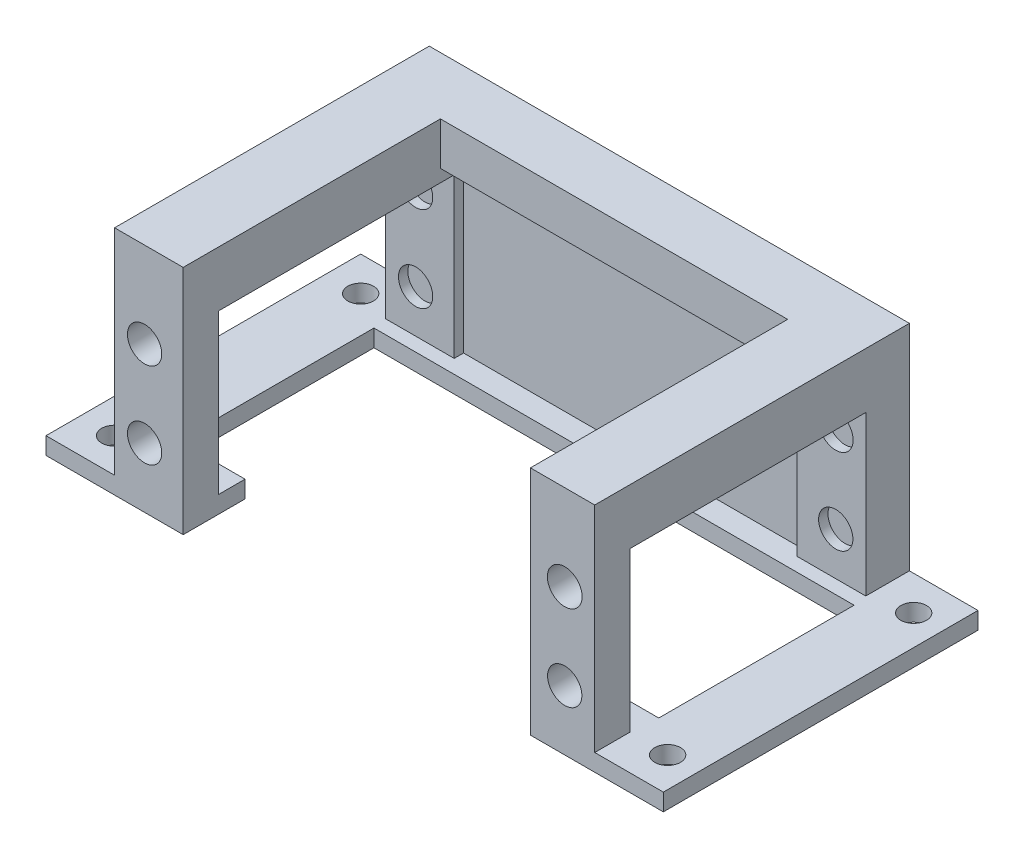
SolidWorks part; units mm, degrees
ref_plane "前视基准面" through (0, 0, 0) normal (0, 0, 1) x (1, 0, 0)
ref_plane "上视基准面" through (0, 0, 0) normal (0, 1, 0) x (1, 0, 0)
ref_plane "右视基准面" through (0, 0, 0) normal (1, 0, 0) x (0, 0, -1)
other "Configuration Table"
sketch "草图1" plane through (0, 0, 0) normal (0, 1, 0) x (1, 0, 0)
  line L1 (0, 0) -> (40, 0)
  line L2 (0, 0) -> (0, 40)
  line L3 (0, 40) -> (40, 40)
  line L4 (40, 0) -> (40, 40)
  dimension "D1" = 40
  dimension "D2" = 40
extrude "凸台-拉伸1" add sketch "草图1" along normal blind 20
sketch "草图2" plane through (0, 0, 0) normal (0, 0, 1) x (1, 0, 0)
  line L0 (0, 10) -> (10, 10)
  line L1 (0, 20) -> (0, 0) construction
  circle A0 centre (10, 10) radius 3
  dimension "D2" = 6
  dimension "D1" = 10
extrude "凸台-拉伸2" add sketch "草图2" along normal blind 4.5
ref_plane "基准面1" through (0, 0, -12.3) normal (0, 0, -1) x (-1, 0, 0)
sketch "草图4" plane through (0, 0, -12.3) normal (0, 0, -1) x (-1, 0, 0)
  line L0 (-1040, 10) -> (48960, 10) construction
  line L1 (-40, 20) -> (-48, 20)
  line L2 (-40, 20) -> (-40, 0)
  line L3 (-40, 0) -> (-48, 0)
  line L4 (-48, 20) -> (-48, 0)
  line L5 (-40, 20) -> (-44.5, 20)
  line L6 (-40, 20) -> (-40, 15)
  line L7 (-40, 15) -> (-44.5, 15)
  line L8 (-44.5, 20) -> (-44.5, 15)
  line L9 (-20, -980) -> (-20, 49020) construction
  line L10 (-40, 20) -> (0, 20) construction
  line L11 (0, 20) -> (0, 0)
  line L12 (0, 0) -> (8, 0)
  line L13 (8, 20) -> (8, 0)
  line L14 (0, 20) -> (8, 20)
  circle A0 centre (-44.5, 15) radius 2
  circle A1 centre (-44.5, 5) radius 2
  circle A2 centre (4.5, 5) radius 2
  circle A3 centre (4.5, 15) radius 2
  point P11 (-40, 10)
  point P19 (-20, 20)
  dimension "D5" = 4
  dimension "D1" = 20
  dimension "D2" = 8
  dimension "D3" = 4.5
  dimension "D4" = 5
extrude "凸台-拉伸4" add sketch "草图4" against normal blind 2.7 contours A0 L8 L1 L4 L3 L2 L7 A1 | A0 L7 L2 L1 L8 | L14 L11 L12 L13 A2 A3
sketch "草图5" plane through (0, 0, 0) normal (-1, 0, 0) x (0, 0, 1)
  line L0 (-40, 10) -> (-35, 10)
  line L1 (-40, 20) -> (-40, 0) construction
  line L3 (-37, 6.5) -> (-33, 6.5)
  line L4 (-37, 6.5) -> (-37, 13.5)
  line L5 (-37, 13.5) -> (-33, 13.5)
  line L6 (-33, 6.5) -> (-33, 13.5)
  line L7 (-37, 6.5) -> (-33, 13.5) construction
  line L8 (-37, 13.5) -> (-33, 6.5) construction
  dimension "D1" = 5
  dimension "D2" = 4
  dimension "D3" = 7
extrude "凸台-拉伸5" add sketch "草图5" along normal blind 7
sketch "草图6" plane through (0, 0, -40) normal (0, 0, -1) x (-1, 0, 0)
  line L1 (-40, 0) -> (8, 0)
  line L2 (-40, 0) -> (-40, 20)
  line L3 (-40, 20) -> (8, 20)
  line L4 (8, 0) -> (8, 20)
extrude "切除-拉伸1" cut sketch "草图6" against normal blind 27.5
sketch "草图7" plane through (0, 0, 0) normal (0, 0, 1) x (1, 0, 0)
  line L1 (0, 20) -> (40, 20)
  line L2 (0, 20) -> (0, 0)
  line L3 (0, 0) -> (40, 0)
  line L4 (40, 20) -> (40, 0)
extrude "切除-拉伸3" cut sketch "草图7" against normal through all both and the other way through all
sketch "草图8" plane through (0, 0, -9.6) normal (0, 0, 1) x (1, 0, 0)
  line L1 (-8, 20) -> (48, 20)
  line L2 (-8, 20) -> (-8, 25)
  line L3 (-8, 25) -> (48, 25)
  line L4 (48, 20) -> (48, 25)
  dimension "D1" = 5
extrude "凸台-拉伸6" add sketch "草图8" against normal blind 2.7
sketch "草图9" plane through (0, 0, -12.3) normal (0, 0, -1) x (-1, 0, 0)
  line L1 (-48, 25) -> (8, 25)
  line L2 (-48, 25) -> (-48, 0)
  line L3 (-48, 0) -> (8, 0)
  line L4 (8, 25) -> (8, 0)
extrude "凸台-拉伸7" add sketch "草图9" along normal blind 30
sketch "草图10" plane through (0, 0, -12.3) normal (0, 0, 1) x (1, 0, 0)
  line L1 (0, 20) -> (40, 20)
  line L2 (0, 20) -> (0, 0)
  line L3 (0, 0) -> (40, 0)
  line L4 (40, 20) -> (40, 0)
extrude "切除-拉伸4" cut sketch "草图10" against normal through all both and the other way through all
sketch "草图11" plane through (0, 0, -9.6) normal (0, 0, 1) x (1, 0, 0)
  circle A0 centre (-4.5, 15) radius 2
  circle A1 centre (-4.5, 5) radius 2
  circle A2 centre (44.5, 15) radius 2.0239
  circle A3 centre (44.5, 5) radius 2
extrude "切除-拉伸5" cut sketch "草图11" against normal through all both and the other way through all
sketch "草图12" plane through (48, 0, 0) normal (1, 0, 0) x (0, 0, -1)
  line L1 (42.3, 0) -> (13.709, 0)
  line L2 (42.3, 0) -> (42.3, 18.5386)
  line L3 (42.3, 18.5386) -> (13.709, 18.5386)
  line L4 (13.709, 0) -> (13.709, 18.5386)
  line L5 (13.709, 18.5386) -> (41.209, 18.5386)
  line L6 (13.709, 18.5386) -> (13.709, 0)
  line L7 (13.709, 0) -> (41.209, 0)
  line L8 (41.209, 18.5386) -> (41.209, 0)
  line M2 (9.6, 0) -> (42.3, 0)
  dimension "D1" = 27.5
extrude "切除-拉伸6" cut sketch "草图12" against normal through all both and the other way through all contours L8 L3 L4 M2
sketch "草图13" plane through (0, 0, -42.3) normal (0, 0, -1) x (-1, 0, 0)
  line L1 (-48, 25) -> (8, 25)
  line L2 (-48, 25) -> (-48, 0)
  line L3 (-48, 0) -> (8, 0)
  line L4 (8, 25) -> (8, 0)
extrude "凸台-拉伸8" add sketch "草图13" along normal blind 4
sketch "草图14" plane through (48, 0, 0) normal (1, 0, 0) x (0, 0, -1)
  line L1 (9.6, 0) -> (46.3, 0)
  line L2 (9.6, 0) -> (9.6, -2)
  line L3 (9.6, -2) -> (46.3, -2)
  line L4 (46.3, 0) -> (46.3, -2)
  dimension "D1" = 2
extrude "凸台-拉伸9" add sketch "草图14" against normal blind 56
sketch "草图15" plane through (48, 0, 0) normal (1, 0, 0) x (0, 0, -1)
  line L1 (9.6, 0) -> (46.3, 0)
  line L2 (9.6, 0) -> (9.6, -2)
  line L3 (9.6, -2) -> (46.3, -2)
  line L4 (46.3, 0) -> (46.3, -2)
extrude "凸台-拉伸10" add sketch "草图15" along normal blind 8
sketch "草图16" plane through (-8, 0, 0) normal (-1, 0, 0) x (0, 0, 1)
  line L1 (-9.6, 0) -> (-46.3, 0)
  line L2 (-9.6, 0) -> (-9.6, -2)
  line L3 (-9.6, -2) -> (-46.3, -2)
  line L4 (-46.3, 0) -> (-46.3, -2)
extrude "凸台-拉伸11" add sketch "草图16" along normal blind 8
sketch "草图17" plane through (0, 20, 0) normal (0, -1, 0) x (1, 0, 0)
  line L1 (0, -9.6) -> (40.5, -9.6)
  line L2 (0, -9.6) -> (0, -39.6)
  line L3 (0, -39.6) -> (40.5, -39.6)
  line L4 (40.5, -9.6) -> (40.5, -39.6)
  dimension "D1" = 40.5
  dimension "D2" = 30
extrude "切除-拉伸7" cut sketch "草图17" against normal through all both and the other way through all
sketch "草图20" plane through (0, -2, 0) normal (0, -1, 0) x (1, 0, 0)
  line L0 (0, -39.6) -> (40.5, -39.6) construction
  line L1 (-7.75, -39.6) -> (48.25, -39.6)
  line L2 (20.25, -39.6) -> (20.25, -16.8178)
  line L3 (-7.75, -16.8178) -> (48.25, -16.8178)
  line L4 (48.25, -39.6) -> (48.25, -16.8178)
  line L5 (-7.75, -39.6) -> (-7.75, -16.8178)
  line M5 (0, -39.6) -> (0, -9.6)
  line M11 (40.5, -9.6) -> (40.5, -39.6)
  dimension "D1" = 28
extrude "切除-拉伸9" cut sketch "草图20" against normal blind 8 contours L5 L1 L3 M5 | L1 L4 L3 M11
sketch "草图21" plane through (0, -2, 0) normal (0, -1, 0) x (1, 0, 0)
  line L0 (20.25, -1039.6) -> (20.25, 48960.4) construction
  line L1 (-16, -46.3) -> (-12, -46.3)
  line L2 (-16, -46.3) -> (-16, -42.3)
  line L3 (-16, -42.3) -> (-12, -42.3)
  line L4 (-12, -46.3) -> (-12, -42.3)
  line L5 (-7.75, -39.6) -> (48.25, -39.6) construction
  line L6 (-1000, -27.459) -> (49000, -27.459) construction
  line L7 (0, -13.709) -> (0, -41.209) construction
  line L9 (-16, -9.6) -> (-12, -9.6)
  line L10 (-16, -9.6) -> (-16, -13.6)
  line L11 (-16, -13.6) -> (-12, -13.6)
  line L12 (-12, -9.6) -> (-12, -13.6)
  circle A0 centre (-12, -42.3) radius 1.5
  circle A1 centre (52.5, -42.3) radius 1.5
  circle A4 centre (-12, -13.6) radius 1.5
  circle A5 centre (52.5, -13.6) radius 1.5
  point P11 (20.25, -39.6)
  point P16 (0, -27.459)
  dimension "D3" = 3
  dimension "D4" = 4
  dimension "D6" = 3
  dimension "D1" = 4
  dimension "D2" = 4
  dimension "D5" = 4
extrude "切除-拉伸10" cut sketch "草图21" against normal through all contours A1 | A5 | A4 | A0
